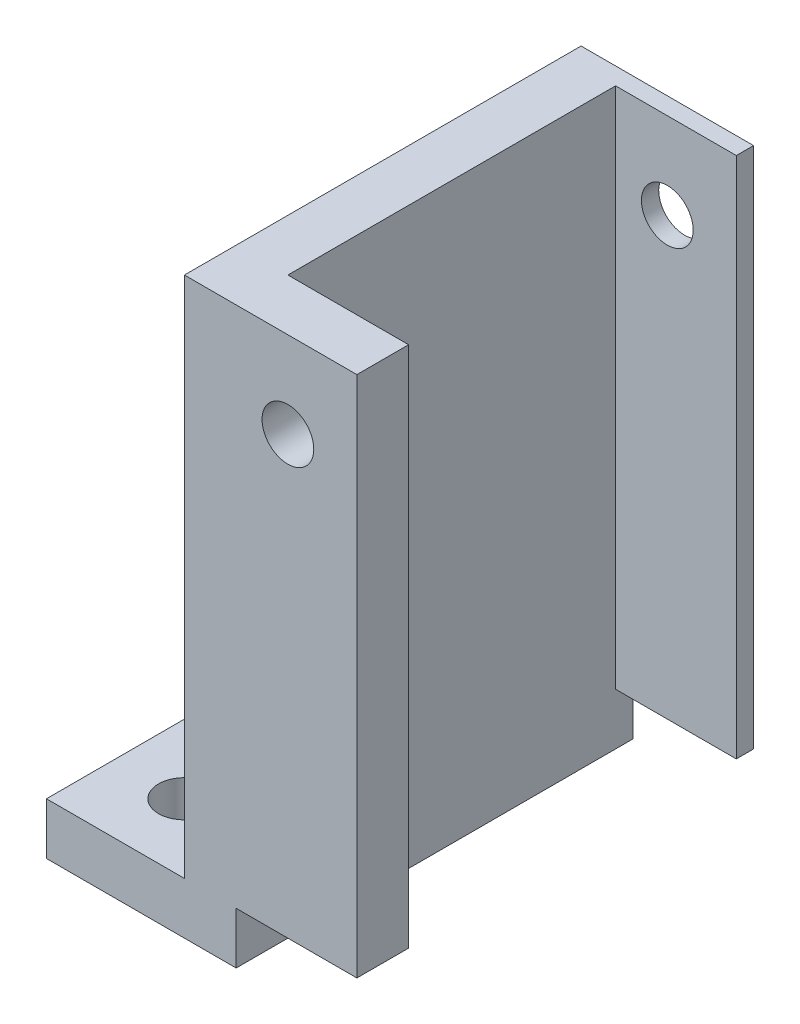
SolidWorks part; units mm, degrees
ref_plane "Alzado" through (0, 0, 0) normal (0, 0, 1) x (1, 0, 0)
ref_plane "Planta" through (0, 0, 0) normal (0, 1, 0) x (1, 0, 0)
ref_plane "Vista lateral" through (0, 0, 0) normal (1, 0, 0) x (0, 0, -1)
sketch "Croquis1" plane through (0, 0, 0) normal (1, 0, 0) x (0, 0, -1)
  line L1 (-23, 0) -> (0, 0)
  line L2 (-23, 0) -> (-23, -30.3)
  line L3 (-23, -30.3) -> (0, -30.3)
  line L4 (0, 0) -> (0, -30.3)
  dimension "D1" = 30.3
  dimension "D2" = 23
extrude "Saliente-Extruir2" add sketch "Croquis1" along normal blind 10
sketch "Croquis3" plane through (0, 0, 0) normal (0, 1, 0) x (1, 0, 0)
  line L0 (10, 0) -> (10, -23) construction
  line L1 (10, -1) -> (3, -1)
  line L2 (10, -1) -> (10, -20)
  line L3 (10, -20) -> (3, -20)
  line L4 (3, -1) -> (3, -20)
  line L5 (10, 0) -> (0, 0) construction
  line L6 (10, -23) -> (0, -23) construction
  line L7 (0, 0) -> (0, -23) construction
  dimension "D1" = 1
  dimension "D2" = 3
  dimension "D3" = 3
extrude "Cortar-Extruir1" cut sketch "Croquis3" against normal through all
sketch "Croquis4" plane through (0, -30.3, 0) normal (0, -1, 0) x (1, 0, 0)
  line L0 (10, 23) -> (0, 23) construction
  line L1 (3, 23) -> (-8, 23)
  line L2 (3, 23) -> (3, 0)
  line L3 (3, 0) -> (-8, 0)
  line L4 (-8, 23) -> (-8, 0)
  line L5 (3, 1) -> (3, 20) construction
  line L6 (10, 0) -> (0, 0) construction
  dimension "D1" = 11
extrude "Saliente-Extruir3" add sketch "Croquis4" along normal blind 3
sketch "Croquis5" plane through (0, -30.3, 0) normal (0, 1, 0) x (1, 0, 0)
  line L0 (-8, -23) -> (-8, 0) construction
  line L2 (-8, 0) -> (0, 0) construction
  line L3 (0, -23) -> (-8, -23) construction
  circle A0 centre (-4, -4) radius 1.5
  circle A1 centre (-4, -19) radius 1.5
  dimension "D1" = 3
  dimension "D2" = 3
  dimension "D3" = 4
  dimension "D4" = 4
  dimension "D5" = 4
  dimension "D6" = 4
extrude "Cortar-Extruir3" cut sketch "Croquis5" against normal through all contours A0 | A1
sketch "Croquis6" plane through (0, 0, 23) normal (0, 0, 1) x (1, 0, 0)
  line L0 (10, 0) -> (10, -30.3) construction
  line L1 (10, 0) -> (0, 0) construction
  circle A0 centre (6, -5) radius 1.5
  dimension "D1" = 3
  dimension "D2" = 4
  dimension "D3" = 5
extrude "Cortar-Extruir4" cut sketch "Croquis6" against normal through all
ref_plane "Plano1" through (0, 0, 11.5) normal (0, 0, 1) x (1, 0, 0)
sketch "Croquis8" plane through (0, 0, 11.5) normal (0, 0, 1) x (1, 0, 0)
  line L0 (-4.9497, -30.3) -> (0, -25.3503)
  line L1 (0, -30.3) -> (-8, -30.3) construction
  line L2 (0, 0) -> (0, -30.3) construction
  dimension "D1" = 45
  dimension "D2" = 7
rib "Nervio1" sketch "Croquis8" sketch "Croquis8" thickness 7 extrusion direction parallel to sketch draft on no parameters "D1"=7
